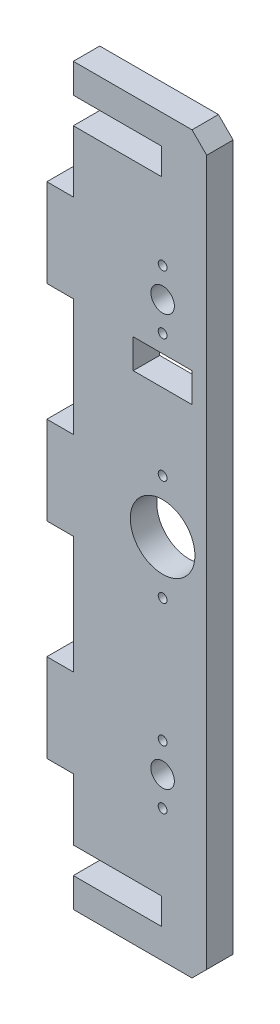
SolidWorks part; units mm, degrees
ref_plane "Front Plane" through (0, 0, 0) normal (0, 0, 1) x (1, 0, 0)
ref_plane "Top Plane" through (0, 0, 0) normal (0, 1, 0) x (1, 0, 0)
ref_plane "Right Plane" through (0, 0, 0) normal (1, 0, 0) x (0, 0, -1)
sketch "Model" plane through (0, 0, 0) normal (0, 0, 1) x (1, 0, 0)
  line L1 (0, 70) -> (0, 110)
  line L2 (40.4, 250) -> (45.4, 245)
  line L3 (45.4, 5) -> (40.4, 0)
  line L8 (40.4, 169) -> (20.4, 169)
  line L9 (40.4, 169) -> (40.4, 179)
  line L10 (40.4, 179) -> (20.4, 179)
  line L11 (20.4, 169) -> (20.4, 179)
  line L34 (45.4, 125) -> (-9, 125) construction
  line L35 (0, 0) -> (40.4, 0)
  line L36 (0, 0) -> (0, 10)
  line L37 (0, 250) -> (40.4, 250)
  line L38 (45.4, 5) -> (45.4, 245)
  line L39 (0, 140) -> (0, 180)
  line L40 (0, 140) -> (-9, 140)
  line L41 (0, 210) -> (-9, 210)
  line L42 (0, 110) -> (-9, 110)
  line L43 (-9, 140) -> (-9, 110)
  line L44 (-9, 210) -> (-9, 180)
  line L45 (0, 180) -> (-9, 180)
  line L46 (0, 70) -> (-9, 70)
  line L47 (-9, 70) -> (-9, 40)
  line L48 (0, 40) -> (-9, 40)
  line L49 (0, 210) -> (0, 231)
  line L51 (30.4, 250) -> (30.4, 0) construction
  line L52 (0, 240) -> (0, 250)
  line L53 (0, 240) -> (30, 240)
  line L54 (30, 10) -> (30, 19)
  line L55 (0, 231) -> (30, 231)
  line L56 (30, 240) -> (30, 231)
  line L57 (0, 19) -> (30, 19)
  line L58 (0, 10) -> (30, 10)
  line L59 (0, 19) -> (0, 40)
  circle A13 centre (30.4, 125) radius 11
  circle A14 centre (30.4, 195) radius 4
  circle A15 centre (30.4, 55) radius 4
  circle A16 centre (30.4, 205) radius 1.5
  circle A17 centre (30.4, 185) radius 1.5
  circle A18 centre (30.4, 65) radius 1.5
  circle A19 centre (30.4, 45) radius 1.5
  circle A20 centre (30.4, 143) radius 1.5
  circle A21 centre (30.4, 107) radius 1.5
  point P0 (30.4, 169)
  dimension "D20" = 22
  dimension "D21" = 8
  dimension "D29" = 3
  dimension "D31" = 3
  dimension "D9" = 9
  dimension "D11" = 30
  dimension "D17" = 250
  dimension "D23" = 70
  dimension "D25" = 9
  dimension "D27" = 30
  dimension "D28" = 10
  dimension "D30" = 10
  dimension "D32" = 18
  dimension "D5" = 30.4
  dimension "D6" = 15
  dimension "D8" = 10
  dimension "D10" = 40
  dimension "D7" = 5
  dimension "D14" = 135
  dimension "D4" = 10
  dimension "D15" = 44
  dimension "D16" = 20
  dimension "D12" = 2
  dimension "D13" = 2
extrude "Boss-Extrude1" add sketch "Model" along normal blind 9
equation "\"material-thickness\" = 9mm"
equation "\"tab-width-large\" = 30mm ' Width of the large version of the Tab"
equation "\"linear-bar-dia\" = 8mm ' Diameter of the metal slide bar used on the X Axis"
equation "\"linear-thread-dia\" = 8mm ' Diameter of the metal threaded rod used on the X Axis"
equation "\"spindle-thread-height\" = 30.4mm ' Height from the base to the spindle for the stepper motor / Servo"
equation "\"spindle-thread-rbearing-diameter\" = 22mm ' Outer diameter of the rotational bearing"
equation "\"D1@Boss-Extrude1\"= \"material-thickness\""
equation "\"D9@Model\"=\"material-thickness\""
equation "\"D11@Model\"=\"tab-width-large\""
equation "\"D21@Model\"=\"linear-bar-dia\""
equation "\"D25@Model\"=\"material-thickness\""
equation "\"D20@Model\"=\"spindle-thread-rbearing-diameter\""
equation "\"D5@Model\"=\"spindle-thread-height\""
